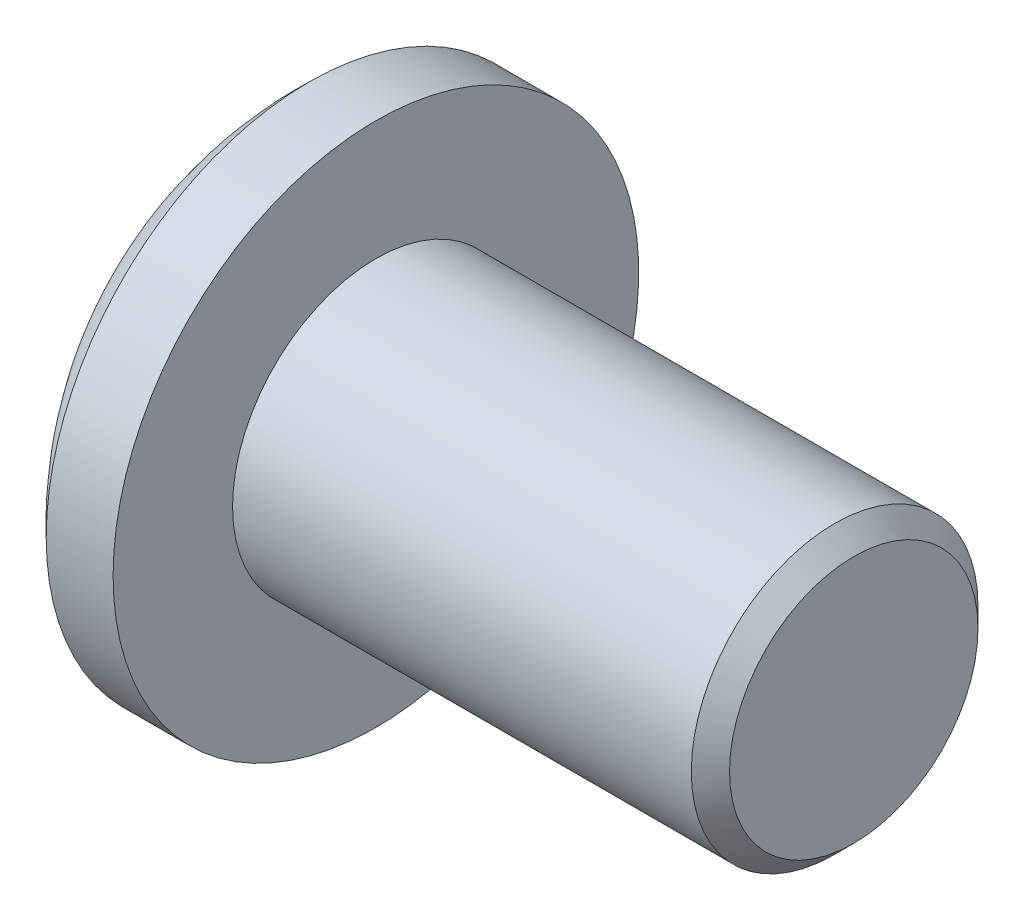
SolidWorks part; units mm, degrees
material "AISI 304"
ref_plane "前视基准面" through (0, 0, 0) normal (0, 0, 1) x (1, 0, 0)
ref_plane "上视基准面" through (0, 0, 0) normal (0, 1, 0) x (1, 0, 0)
ref_plane "右视基准面" through (0, 0, 0) normal (1, 0, 0) x (0, 0, -1)
other "Configuration Table"
sketch "草图1" plane through (0, 0, 0) normal (0, 0, 1) x (1, 0, 0)
  line L0 (0, 0) -> (14.9561, 0) construction
  line L1 (1.2, 2.75) -> (1.9, 2.75)
  line L2 (1.9, 2.75) -> (1.9, 1.5)
  line L3 (1.9, 1.5) -> (6.9, 1.5)
  line L4 (6.9, 1.5) -> (6.9, 0)
  line L5 (6.9, 0) -> (0, 0)
  line L6 (0, 0) -> (0, 3.4547) construction
  arc A0 (1.2, 2.75) -> (0, 0) centre (3.751, 0) ccw
  dimension "D1" = 3
  dimension "D2" = 5
  dimension "D3" = 5.5
  dimension "D4" = 1.9
  dimension "D5" = 0.7
revolve "旋转1" add sketch "草图1" angle 360 about L0
cosmetic thread "装饰螺纹线1" parameters "D2"=2
sketch "草图2" plane through (1.9, 0, 0) normal (1, 0, 0) x (0, 0, -1)
  line L0 (0.35, -0.35) -> (0.35, -1.5)
  line L1 (1.5, 0.35) -> (0.35, 0.35)
  line L2 (1.5, 0.35) -> (1.5, -0.35)
  line L3 (1.5, -0.35) -> (0.35, -0.35)
  line L4 (-1.5, 0.35) -> (-1.5, -0.35)
  line L5 (1.5, 0.35) -> (-1.5, -0.35) construction
  line L6 (1.5, -0.35) -> (-1.5, 0.35) construction
  line L7 (0.35, 1.5) -> (-0.35, 1.5)
  line L8 (0.35, 1.5) -> (0.35, 0.35)
  line L9 (0.35, -1.5) -> (-0.35, -1.5)
  line L10 (-0.35, 1.5) -> (-0.35, 0.35)
  line L11 (0.35, 1.5) -> (-0.35, -1.5) construction
  line L12 (0.35, -1.5) -> (-0.35, 1.5) construction
  line L13 (-0.35, -0.35) -> (-1.5, -0.35)
  line L14 (-0.35, -0.35) -> (-0.35, -1.5)
  line L15 (-0.35, 0.35) -> (-1.5, 0.35)
  point P0 (0, 0)
  point P5 (0, 0)
  dimension "D1" = 3
  dimension "D2" = 0.7
  dimension "D3" = 0.7
  dimension "D4" = 3
extrude "切除-拉伸1" cut sketch "草图2" against normal through all from offset 0.5 offset against normal yes
sketch "草图3" plane through (0, 0, 0) normal (0, 0, 1) x (1, 0, 0)
  line L0 (1.9, 0) -> (1.9, 2)
  line L1 (1.9, -2.75) -> (1.9, 2.75) construction
  line L2 (1.9, 2) -> (0.9, 2)
  line L4 (0, 0) -> (7.4583, 0) construction
  line L7 (0.3308, 1.5) -> (1.4, 1.5) construction
  line L8 (0.9, 2) -> (1.4, 0)
  line L9 (1.4, 0) -> (1.9, 0)
  dimension "D1" = 1
  dimension "D2" = 0.5
  dimension "D4" = 0.5
revolve "旋转3" add sketch "草图3" angle 360 about L4
chamfer "倒角1" distance 0.2 angle 45 1 edges at (6.9, 0, 1.5)
equation "\"。5\"=0.27967"
